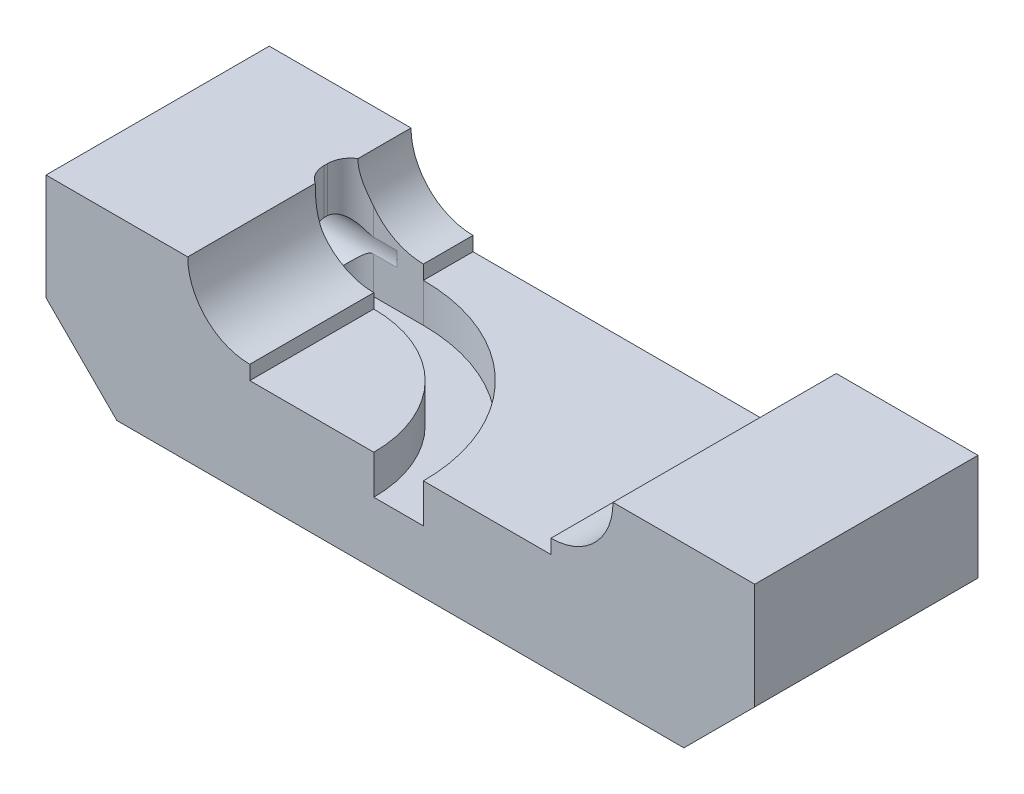
SolidWorks part; units mm, degrees
ref_plane "Front Plane" through (0, 0, 0) normal (0, 0, 1) x (1, 0, 0)
ref_plane "Top Plane" through (0, 0, 0) normal (0, 1, 0) x (1, 0, 0)
ref_plane "Right Plane" through (0, 0, 0) normal (1, 0, 0) x (0, 0, -1)
sketch "Sketch1" plane through (0, 0, 0) normal (0, 1, 0) x (1, 0, 0)
  line L1 (-12.7, -4.0005) -> (12.7, -4.0005)
  line L2 (-12.7, -4.0005) -> (-12.7, 4.0005)
  line L3 (-12.7, 4.0005) -> (12.7, 4.0005)
  line L4 (12.7, -4.0005) -> (12.7, 4.0005)
  line L5 (-12.7, -4.0005) -> (12.7, 4.0005) construction
  line L6 (-12.7, 4.0005) -> (12.7, -4.0005) construction
  point P0 (0, 0)
  dimension "D1" = 25.4
  dimension "D2" = 8.001
extrude "Boss-Extrude1" add sketch "Sketch1" along normal blind 6.35
sketch "Sketch2" plane through (0, 0, -4.0005) normal (0, 0, -1) x (-1, 0, 0)
  line L0 (5.3975, 6.35) -> (-5.3975, 6.35) construction
  line L1 (5.3975, 4.1275) -> (-5.3975, 4.1275)
  line L2 (5.3975, 8.5725) -> (-5.3975, 8.5725)
  line L3 (12.7, 6.35) -> (-12.7, 6.35) construction
  line L4 (-12.7, 0) -> (12.7, 0) construction
  line L6 (12.7, 6.35) -> (12.7, 0) construction
  line L7 (-12.7, 6.35) -> (-12.7, 0) construction
  arc A0 (5.3975, 4.1275) -> (5.3975, 8.5725) centre (5.3975, 6.35) ccw
  arc A1 (-5.3975, 8.5725) -> (-5.3975, 4.1275) centre (-5.3975, 6.35) ccw
  point P2 (0, 6.35)
  dimension "D1" = 6.35
  dimension "D2" = 10.795
  dimension "D3" = 4.445
extrude "Cut-Extrude1" cut sketch "Sketch2" against normal blind 25.4
ref_plane "Plane1" through (0, 4.1275, 0) normal (0, 1, 0) x (1, 0, 0)
sketch "Sketch4" plane through (0, 4.1275, 0) normal (0, 1, 0) x (1, 0, 0)
  line L1 (0.8255, -4.0005) -> (-0.9525, -4.0005)
  line L2 (-5.3975, 0.4445) -> (-7.1855, 0.4445)
  line L3 (-8.011, 1.27) -> (-8.011, 1.397)
  line L4 (-7.1855, 2.2225) -> (-5.3975, 2.2225)
  arc A0 (-0.9525, -4.0005) -> (-5.3975, 0.4445) centre (-5.3975, -4.0005) ccw
  arc A1 (0.8255, -4.0005) -> (-5.3975, 2.2225) centre (-5.3975, -4.0005) ccw
  arc A2 (-8.011, 1.27) -> (-7.1855, 0.4445) centre (-7.1855, 1.27) ccw
  arc A3 (-7.1855, 2.2225) -> (-8.011, 1.397) centre (-7.1855, 1.397) ccw
  dimension "D1" = 8.89
  dimension "D2" = 12.446
  dimension "D3" = 2.6135
  dimension "D4" = 1.778
  dimension "D5" = 0.8255
extrude "Cut-Extrude2" cut sketch "Sketch4" against normal blind 1.905 and the other way through all
ref_plane "Plane3" through (-12.7, 0, 0) normal (-1, 0, 0) x (0, 0, 1)
sketch "Sketch5" plane through (12.7, 0, 0) normal (1, 0, 0) x (0, 0, -1)
  line L0 (-4.0005, 6.35) -> (-4.0005, 0) construction
  line L1 (-4.0005, 6.35) -> (4.0005, 6.35) construction
  circle A0 centre (1.3335, 3.81) radius 0.9271
  dimension "D2" = 1.8542
  dimension "D1" = 5.334
  dimension "D3" = 2.54
extrude "Cut-Extrude3" cut sketch "Sketch5" along normal blind 6.35 from surface at -25.4 starting at plane "Plane3"
fillet "Fillet3" [suppressed] radius 6.35
sketch "Sketch6" plane through (0, 4.1275, 0) normal (0, 1, 0) x (1, 0, 0)
  line L1 (5.3975, -4.0005) -> (-5.3975, -4.0005)
  line L2 (5.3975, -4.0005) -> (5.3975, 4.0005)
  line L3 (5.3975, 4.0005) -> (-5.3975, 4.0005)
  line L4 (-5.3975, -4.0005) -> (-5.3975, 4.0005)
extrude "Cut-Extrude4" cut sketch "Sketch6" against normal blind 0.508
chamfer "Chamfer1" distance 2.54 angle 45 2 edges at (-12.7, 0, 0) (12.7, 0, 0)
